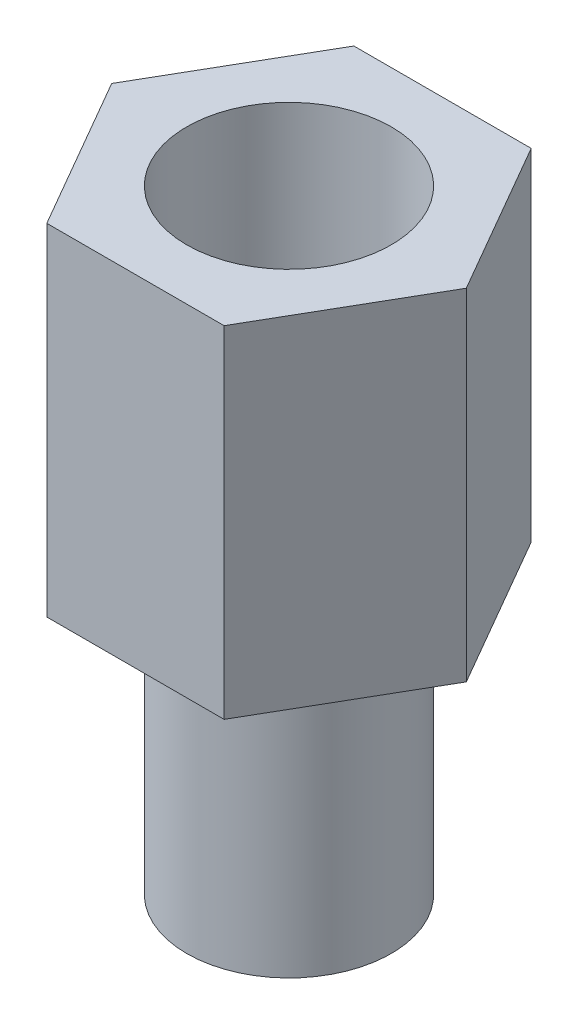
SolidWorks part; units mm, degrees
material "黄铜"
ref_plane "前视基准面" through (0, 0, 0) normal (0, 0, 1) x (1, 0, 0)
ref_plane "上视基准面" through (0, 0, 0) normal (0, 1, 0) x (1, 0, 0)
ref_plane "右视基准面" through (0, 0, 0) normal (1, 0, 0) x (0, 0, -1)
other "Configuration Table"
sketch "草图1" plane through (0, 0, 0) normal (0, 1, 0) x (1, 0, 0)
  line L1 (2.6, 0) -> (1.3, 2.2517)
  line L2 (1.3, 2.2517) -> (-1.3, 2.2517)
  line L3 (-1.3, 2.2517) -> (-2.6, 0)
  line L4 (-2.6, 0) -> (-1.3, -2.2517)
  line L5 (-1.3, -2.2517) -> (1.3, -2.2517)
  line L6 (1.3, -2.2517) -> (2.6, 0)
  circle A0 centre (0, 0) radius 2.6 construction
  dimension "D1" = 4.5033
extrude "凸台-拉伸1" add sketch "草图1" along normal blind 5
sketch "草图2" plane through (0, 5, 0) normal (0, 1, 0) x (1, 0, 0)
  circle A0 centre (0, 0) radius 1.5
extrude "切除-拉伸1" cut sketch "草图2" against normal blind 3.5
sketch "草图3" plane through (0, 0, 0) normal (0, -1, 0) x (1, 0, 0)
  circle A0 centre (0, 0) radius 1.5
extrude "凸台-拉伸2" add sketch "草图3" along normal blind 4
